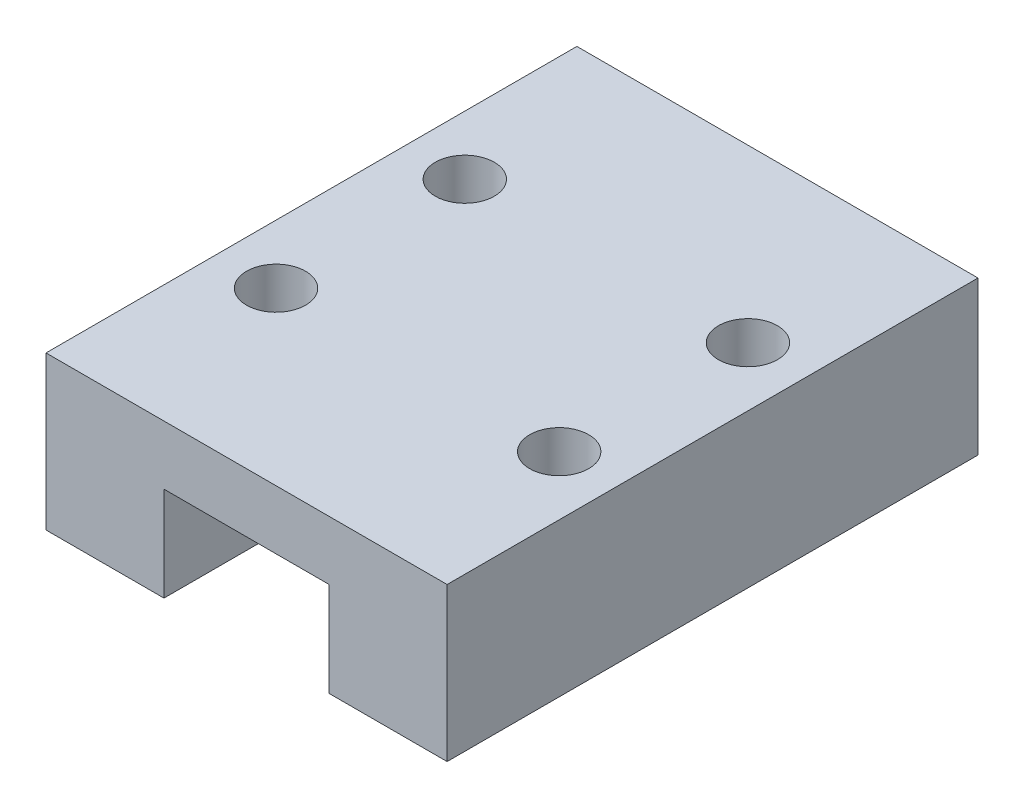
SolidWorks part; units mm, degrees
ref_plane "Front Plane" through (0, 0, 0) normal (0, 0, 1) x (1, 0, 0)
ref_plane "Top Plane" through (0, 0, 0) normal (0, 1, 0) x (1, 0, 0)
ref_plane "Right Plane" through (0, 0, 0) normal (1, 0, 0) x (0, 0, -1)
sketch "Sketch1" plane through (0, 0, 0) normal (0, 0, 1) x (1, 0, 0)
  line L0 (12, 0) -> (17, 0)
  line L1 (0, 0) -> (5, 0)
  line L2 (0, 0) -> (0, 6.5)
  line L3 (0, 6.5) -> (17, 6.5)
  line L4 (17, 0) -> (17, 6.5)
  line L6 (5, 0) -> (5, 4)
  line L7 (5, 4) -> (12, 4)
  line L8 (12, 0) -> (12, 4)
  line L9 (8.5, 0) -> (12, 4) construction
  line L10 (5, 4) -> (8.5, 0) construction
  point P5 (8.5, 0)
  dimension "D1" = 17
  dimension "D2" = 6.5
  dimension "D3" = 4
  dimension "D4" = 7
extrude "Boss-Extrude1" add sketch "Sketch1" along normal blind 22.5
sketch "Sketch2" plane through (0, 6.5, 0) normal (0, 1, 0) x (1, 0, 0)
  line L0 (8.5, 0) -> (8.5, -22.5) construction
  line L1 (17, 0) -> (0, 0) construction
  line L2 (17, -22.5) -> (0, -22.5) construction
  line L4 (2.5, -15.25) -> (14.5, -15.25) construction
  line L5 (2.5, -15.25) -> (2.5, -7.25) construction
  line L6 (2.5, -7.25) -> (14.5, -7.25) construction
  line L7 (14.5, -15.25) -> (14.5, -7.25) construction
  line L8 (2.5, -15.25) -> (14.5, -7.25) construction
  line L9 (2.5, -7.25) -> (14.5, -15.25) construction
  circle A0 centre (14.5, -7.25) radius 1.25
  circle A1 centre (2.5, -7.25) radius 1.25
  circle A2 centre (2.5, -15.25) radius 1.25
  circle A3 centre (14.5, -15.25) radius 1.25
  point P6 (8.5, -11.25)
  dimension "D3" = 2.5
  dimension "D1" = 12
  dimension "D2" = 8
extrude "Cut-Extrude1" cut sketch "Sketch2" against normal blind 3
